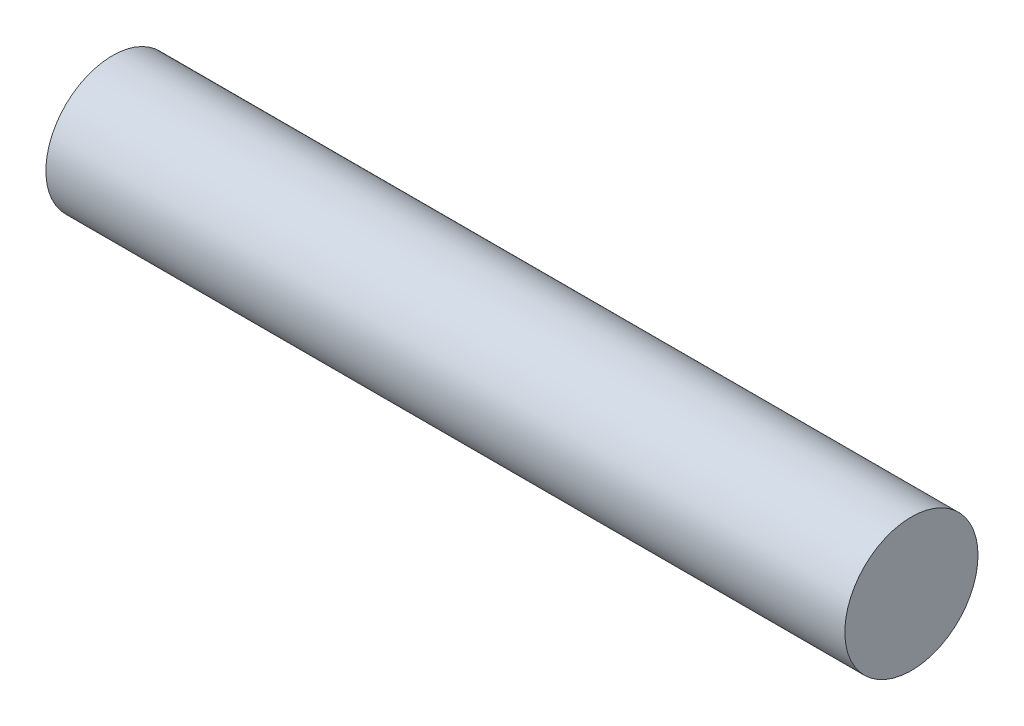
SolidWorks part; units mm, degrees
ref_plane "Ön Düzlem" through (0, 0, 0) normal (0, 0, 1) x (1, 0, 0)
ref_plane "Üst Düzlem" through (0, 0, 0) normal (0, 1, 0) x (1, 0, 0)
ref_plane "Sağ Düzlem" through (0, 0, 0) normal (1, 0, 0) x (0, 0, -1)
sketch "Sketch1" plane through (0, 0, 0) normal (1, 0, 0) x (0, 0, -1)
  circle A0 centre (-68.1919, 15.1529) radius 25
extrude "Boss-Extrude1" add sketch "Sketch1" along normal blind 300
